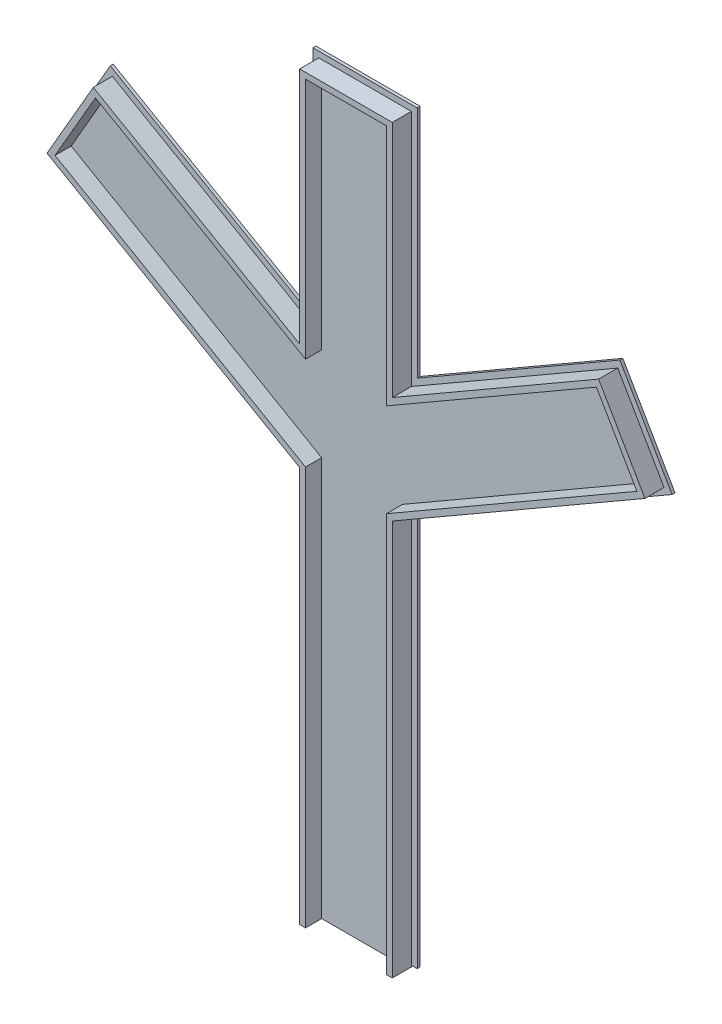
SolidWorks part; units mm, degrees
ref_plane "Спереди" through (0, 0, 0) normal (0, 0, 1) x (1, 0, 0)
ref_plane "Сверху" through (0, 0, 0) normal (0, 1, 0) x (1, 0, 0)
ref_plane "Справа" through (0, 0, 0) normal (1, 0, 0) x (0, 0, -1)
sketch "Sketch1" plane through (0, 0, 0) normal (0, 0, 1) x (1, 0, 0)
  line L0 (-5.5, 17) -> (-5.5, 71.2983)
  line L1 (-5.5, 117) -> (5.5, 117)
  line L2 (-5.5, 84) -> (-34.0788, 100.5)
  line L3 (-34.0788, 100.5) -> (-39.5788, 90.9737)
  line L4 (-39.5788, 90.9737) -> (-5.5, 71.2983)
  line L5 (-5.5, 84) -> (-5.5, 117)
  line L6 (0, 13.8176) -> (0, -11.7579) construction
  line L7 (5.5, 84) -> (5.5, 117)
  line L8 (39.5788, 90.9737) -> (5.5, 71.2983)
  line L9 (34.0788, 100.5) -> (39.5788, 90.9737)
  line L10 (5.5, 84) -> (34.0788, 100.5)
  line L11 (5.5, 17) -> (5.5, 71.2983)
  line L12 (-6.3, 17) -> (-6.3, 70.8364)
  line L13 (-40.6717, 90.6809) -> (-6.3, 70.8364)
  line L14 (-34.3717, 101.5928) -> (-40.6717, 90.6809)
  line L15 (-6.3, 85.3856) -> (-34.3717, 101.5928)
  line L16 (-6.3, 85.3856) -> (-6.3, 117.8)
  line L17 (-6.3, 117.8) -> (6.3, 117.8)
  line L18 (6.3, 85.3856) -> (6.3, 117.8)
  line L19 (6.3, 85.3856) -> (34.3717, 101.5928)
  line L20 (34.3717, 101.5928) -> (40.6717, 90.6809)
  line L21 (40.6717, 90.6809) -> (6.3, 70.8364)
  line L22 (6.3, 17) -> (6.3, 70.8364)
  line L23 (-6.3, 17) -> (-5.5, 17)
  line L24 (5.5, 17) -> (6.3, 17)
  point P15 (0, 117)
  point P28 (0, 0)
  dimension "D1" = 100
  dimension "D2" = 11
  dimension "D3" = 5.5
  dimension "D4" = 60
  dimension "D5" = 90
  dimension "D6" = 33
  dimension "D7" = 0.8
  dimension "D8" = 17
extrude "Boss-Extrude1" add sketch "Sketch1" along normal blind 3
sketch "Sketch2" plane through (0, 0, 0) normal (0, 0, 1) x (1, 0, 0)
  line L0 (-5.5, 17) -> (-5.5, 71.2983)
  line L1 (-5.5, 71.2983) -> (-39.5788, 90.9737)
  line L2 (-39.5788, 90.9737) -> (-34.0788, 100.5)
  line L3 (-34.0788, 100.5) -> (-5.5, 84)
  line L4 (-5.5, 84) -> (-5.5, 117)
  line L5 (-5.5, 117) -> (5.5, 117)
  line L6 (5.5, 117) -> (5.5, 84)
  line L7 (5.5, 84) -> (34.0788, 100.5)
  line L8 (34.0788, 100.5) -> (39.5788, 90.9737)
  line L9 (39.5788, 90.9737) -> (5.5, 71.2983)
  line L10 (5.5, 71.2983) -> (5.5, 17)
  line L11 (5.5, 71.2983) -> (5.5, 17) construction
  line L12 (5.5, 17) -> (-5.5, 17)
extrude "Boss-Extrude2" add sketch "Sketch2" along normal blind 0.8
sketch "Sketch3" plane through (0, 0, 0) normal (0, 0, 1) x (1, 0, 0)
  line L0 (-6.3, 17.2) -> (-6.3, 70.8364)
  line L1 (-6.3, 70.8364) -> (-40.6717, 90.6809)
  line L2 (-40.6717, 90.6809) -> (-34.3717, 101.5928)
  line L3 (-34.3717, 101.5928) -> (-6.3, 85.3856)
  line L4 (-6.3, 85.3856) -> (-6.3, 117.8)
  line L5 (-6.3, 117.8) -> (6.3, 117.8)
  line L6 (6.3, 117.8) -> (6.3, 85.3856)
  line L7 (6.3, 85.3856) -> (34.3717, 101.5928)
  line L8 (34.3717, 101.5928) -> (40.6717, 90.6809)
  line L9 (40.6717, 90.6809) -> (6.3, 70.8364)
  line L10 (6.3, 70.8364) -> (6.3, 17.2)
  line L11 (-7.1, 17.2) -> (-7.1, 70.3745)
  line L12 (-7.1, 70.3745) -> (-41.7645, 90.3881)
  line L13 (-41.7645, 90.3881) -> (-34.6645, 102.6856)
  line L14 (-34.6645, 102.6856) -> (-7.1, 86.7713)
  line L15 (-7.1, 86.7713) -> (-7.1, 118.6)
  line L16 (-7.1, 118.6) -> (7.1, 118.6)
  line L17 (7.1, 118.6) -> (7.1, 86.7713)
  line L18 (7.1, 86.7713) -> (34.6645, 102.6856)
  line L19 (34.6645, 102.6856) -> (41.7645, 90.3881)
  line L20 (41.7645, 90.3881) -> (7.1, 70.3745)
  line L21 (7.1, 70.3745) -> (7.1, 17.2)
  line L22 (7.1, 70.3745) -> (7.1, 17) construction
  line L23 (6.3, 70.8364) -> (6.3, 17) construction
  line L24 (-7.1, 17.2) -> (-6.3, 17.2)
  line L25 (6.3, 17.2) -> (7.1, 17.2)
  line L26 (-7.1, 17) -> (-7.1, 70.3745) construction
  line L27 (-6.3, 17) -> (-6.3, 70.8364) construction
  dimension "D1" = 0.8
  dimension "D2" = 0.2
extrude "Boss-Extrude3" add sketch "Sketch3" along normal blind 0.4
